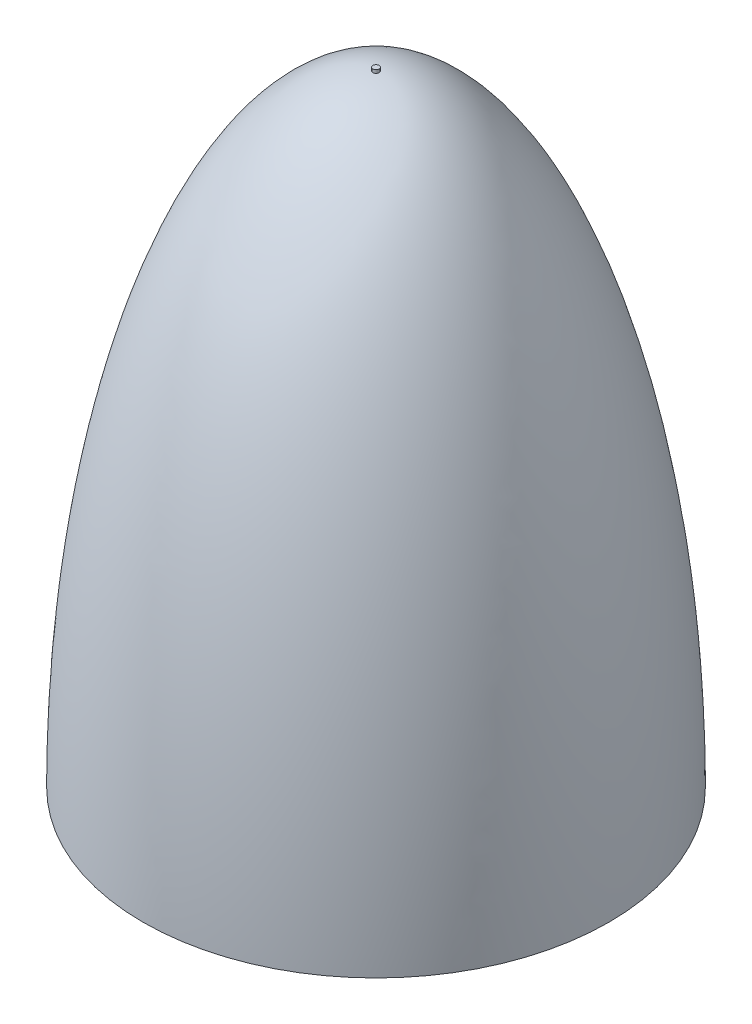
SolidWorks part; units mm, degrees
material "Perspex (TM) GS Acrylic Cast Sheet"
ref_plane "Front Plane" through (0, 0, 0) normal (0, 0, 1) x (1, 0, 0)
ref_plane "Top Plane" through (0, 0, 0) normal (0, 1, 0) x (1, 0, 0)
ref_plane "Right Plane" through (0, 0, 0) normal (1, 0, 0) x (0, 0, -1)
sketch "Sketch1" plane through (0, 0, 0) normal (0, 0, 1) x (1, 0, 0)
  line L0 (0, 0) -> (0, -800)
  line L1 (0, -800) -> (300, -800)
  line L2 (300, -800) -> (0, 0)
  line L3 (4, 0) -> (4, -0.0711)
  line L4 (0, 0) -> (4, 0)
  line L5 (0, 0) -> (0, 4)
  line L6 (0, 4) -> (4, 4)
  line L7 (4, 0) -> (4, 4)
  ellipse E0 centre (0, -800) end of major axis (0, 0) minor radius 300
  dimension "D1" = 300
  dimension "D2" = 800
  dimension "D3" = 0
  dimension "D4" = 4
  dimension "D5" = 4
revolve "Revolve1" add sketch "Sketch1" angle 360 about L0
